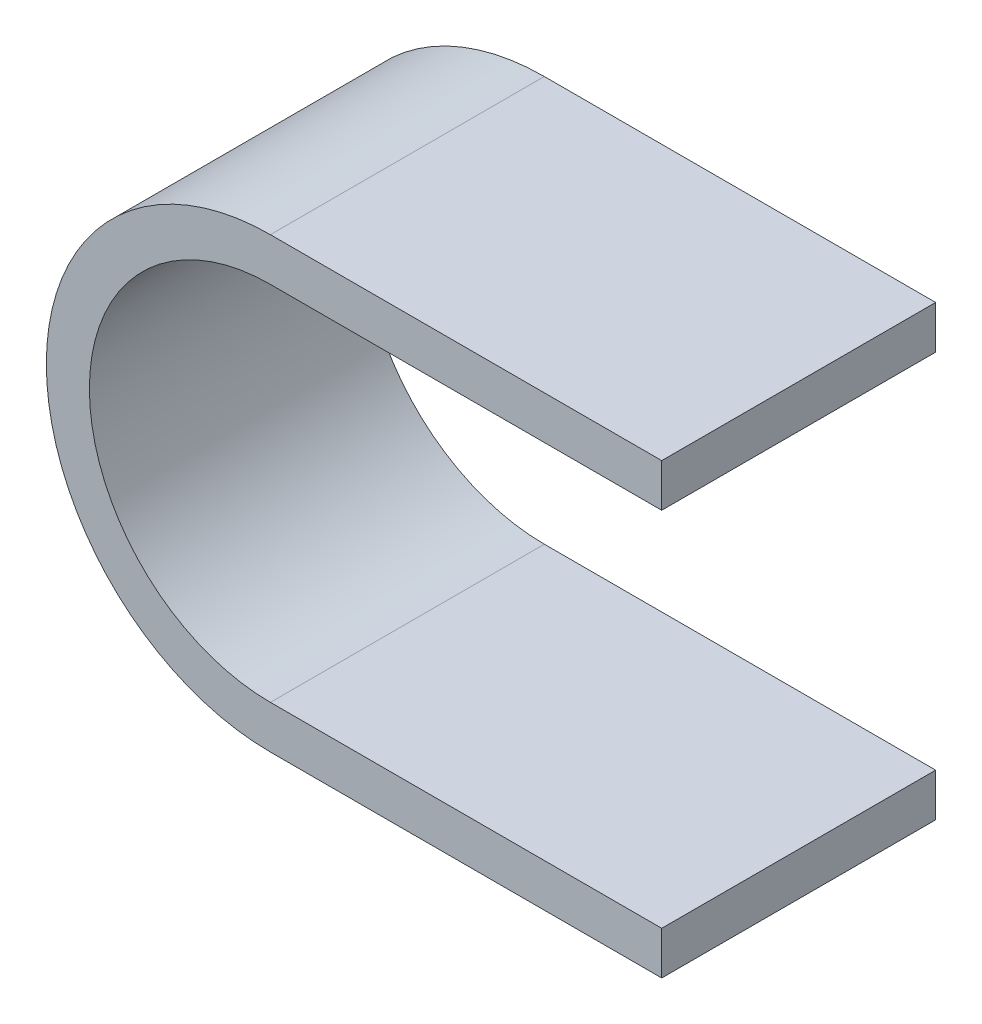
SolidWorks part; units mm, degrees
ref_plane "Front Plane" through (0, 0, 0) normal (0, 0, 1) x (1, 0, 0)
ref_plane "Top Plane" through (0, 0, 0) normal (0, 1, 0) x (1, 0, 0)
ref_plane "Right Plane" through (0, 0, 0) normal (1, 0, 0) x (0, 0, -1)
sketch "Sketch1" plane through (0, 0, 0) normal (0, 0, 1) x (1, 0, 0)
  line L0 (0, 18.5) -> (40, 18.5)
  line L1 (0, -18.5) -> (40, -18.5)
  line L2 (0, 22.9) -> (40, 22.9)
  line L3 (40, 22.9) -> (40, 18.5)
  line L4 (0, -22.9) -> (40, -22.9)
  line L5 (40, -22.9) -> (40, -18.5)
  circle A0 centre (0, 0) radius 18.5
  circle A1 centre (0, 0) radius 22.9
  dimension "D1" = 37
  dimension "D3" = 40
  dimension "D4" = 40
  dimension "D2" = 4.4
extrude "Boss-Extrude1" add sketch "Sketch1" along normal blind 28 contours A1 L0 L3 L2 | L0 A1 L1 A0 | A1 L4 L5 L1
